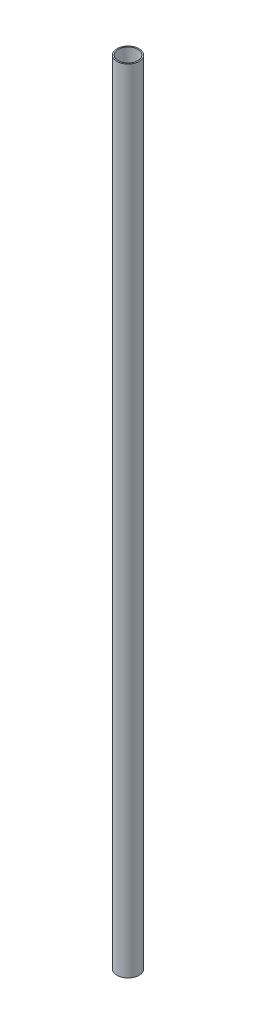
SolidWorks part; units mm, degrees
material "Manual Density from Real Component Tube FWD"
ref_plane "Piano frontale" through (0, 0, 0) normal (0, 0, 1) x (1, 0, 0)
ref_plane "Piano superiore" through (0, 0, 0) normal (0, 1, 0) x (1, 0, 0)
ref_plane "Piano destro" through (0, 0, 0) normal (1, 0, 0) x (0, 0, -1)
sketch "Schizzo1" plane through (0, 0, 0) normal (0, 1, 0) x (1, 0, 0)
  circle A0 centre (0, 0) radius 9
  circle A1 centre (0, 0) radius 8
  dimension "D1" = 18
  dimension "D2" = 16
extrude "Estrusione-Estrusione1" add sketch "Schizzo1" along normal blind 645
ref_plane "PianoTangenteSuperiore" through (0, 0, -9) normal (0, 0, -1) x (-1, 0, 0)
